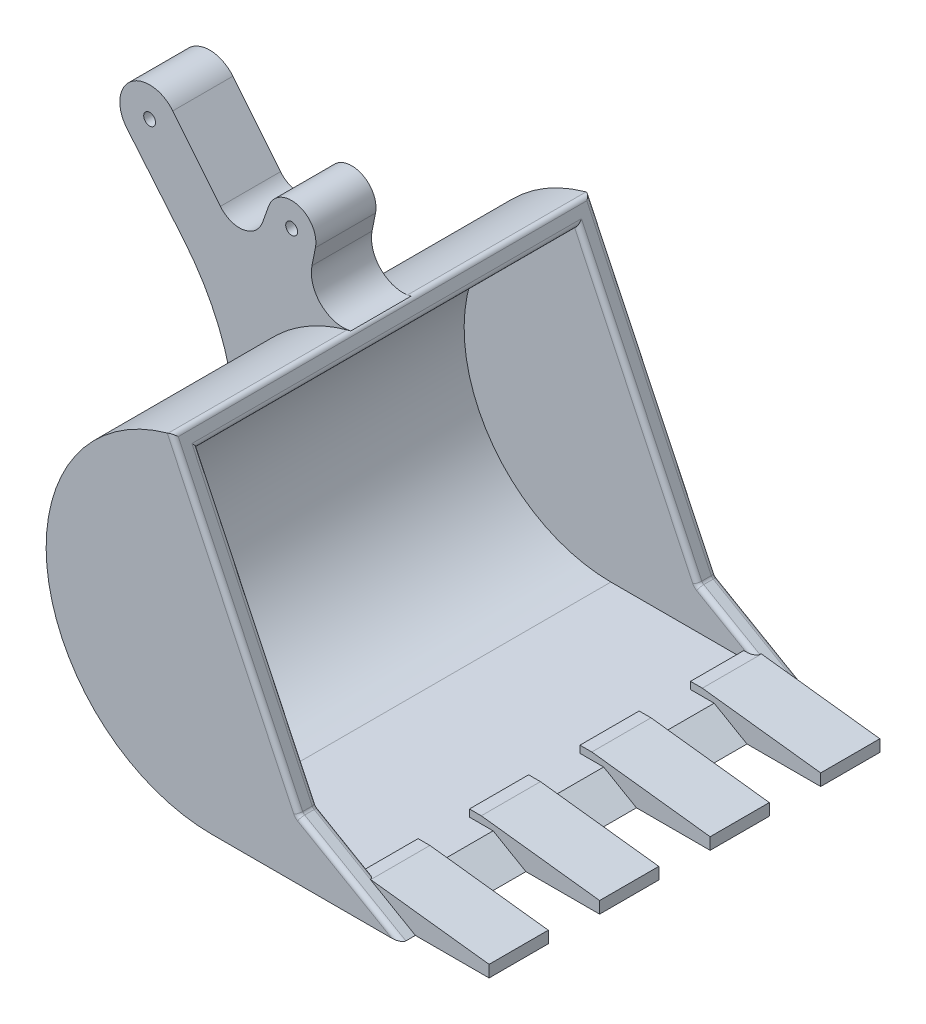
SolidWorks part; units mm, degrees
material "Alloy Steel"
ref_plane "Front Plane" through (0, 0, 0) normal (0, 0, 1) x (1, 0, 0)
ref_plane "Top Plane" through (0, 0, 0) normal (0, 1, 0) x (1, 0, 0)
ref_plane "Right Plane" through (0, 0, 0) normal (1, 0, 0) x (0, 0, -1)
other "Center of Mass"
sketch "Sketch3" plane through (0, 0, 0) normal (0, 0, 1) x (1, 0, 0)
  line L1 (-323.5598, 25) -> (-280.2585, 0)
  line L2 (-360.2585, 0) -> (-280.2585, 0)
  line L6 (-323.5598, 25) -> (-377.1418, 137.9334)
  arc A0 (-360.2585, 0) -> (-377.1418, 137.9334) centre (-360.2585, 70) cw
  point P0 (-355.0693, 139.8074)
  dimension "D1" = 70
  dimension "D2" = 125
  dimension "D3" = 80
  dimension "D4" = 50
  dimension "D5" = 30
extrude "Boss-Extrude1" add sketch "Sketch3" along normal blind 75 and the other way blind 101.6
shell "Shell2" thickness 8
sketch "Sketch5" plane through (0, 0, 0) normal (0, 0, 1) x (1, 0, 0)
  line L0 (-471.8112, 164.8752) -> (-447.6261, 135.8549)
  line L1 (-392.0864, 160.922) -> (-393.5507, 153.6017)
  line L2 (-452.3551, 180.8486) -> (-432.2396, 155.9766)
  line L3 (-411.7956, 166.3923) -> (-414.4462, 158.9945)
  arc A0 (-377.1418, 137.9334) -> (-360.2585, 0) centre (-360.2585, 70) ccw construction
  arc A1 (-432.2396, 155.9766) -> (-414.4462, 158.9945) centre (-424.191, 162.486) ccw
  arc A2 (-427.0333, 91.003) -> (-377.1418, 137.9334) centre (-360.2585, 70) cw
  arc A3 (-452.3551, 180.8486) -> (-471.8112, 164.8752) centre (-462.1418, 172.9334) ccw
  arc A5 (-411.7956, 166.3923) -> (-392.0864, 160.922) centre (-402.1418, 162.9334) cw
  arc A6 (-393.5507, 153.6017) -> (-377.1418, 137.9334) centre (-380.3811, 150.9674) ccw
  arc A8 (-447.6261, 135.8549) -> (-427.0333, 91.003) centre (-520.1798, 75.39) cw
  point P3 (-335.5895, 182.9557)
  point P4 (-378.4966, 174.1952)
  point P7 (0, 0)
  point P9 (-348.1459, 131.2286)
  point P15 (-366.2029, 207.3007)
  point P18 (-380.0938, 170.9707)
  point P20 (-395.534, 191.1792)
  point P22 (-312.6562, 175.5119)
  point P23 (-377.8231, 168.473)
  point P24 (-372.6404, 208.663)
  point P25 (0, 0)
  point P27 (-453.7481, 155.9016)
  point P28 (-453.5686, 177.9334)
  point P29 (-460.077, 153.2208)
  point P30 (0, 0)
  point P31 (-435.4582, 161.0396)
  point P32 (-451.5955, 172.9334)
  point P34 (-442.2496, 158.7758)
  point P35 (-416.7819, 157.4678)
  point P36 (-449.5549, 172.9334)
  point P37 (-434.6093, 159.7785)
  point P38 (-455.2665, 143.2122)
  point P39 (-427.0333, 91.003)
  point P43 (-447.6261, 135.8549)
  point P44 (-396.168, 152.5647)
  point P45 (0, 0)
  point P46 (-419.881, 155.7953)
  point P47 (-408.4001, 165.5007)
  point P48 (-395.1358, 161.463)
  point P49 (-395.6931, 155.0151)
  point P50 (-418.8686, 155.9766)
  point P51 (-411.7956, 166.3923)
  dimension "D1" = 25
  dimension "D3" = 35
  dimension "D5" = 60
  dimension "D6" = 25
extrude "Boss-Extrude2" add sketch "Sketch5" along normal mid plane 25.4 separate body contours A3 L0 A8 A2 A6 L1 A5 L3 A1 L2
sketch "Sketch8" plane through (0, 0, 0) normal (0, 0, 1) x (1, 0, 0)
  circle A0 centre (-402.1418, 162.9334) radius 2.5
  circle A1 centre (-462.1418, 172.9334) radius 2.5
  dimension "D1" = 5
  dimension "D2" = 5
extrude "Cut-Extrude1" cut sketch "Sketch8" against normal blind 20 and the other way blind 20
move or copy body "Body-Move/Copy4" bodies to move or copy 103 copy no translate (0, 0, -13.3)
move or copy body "Body-Move/Copy6" [suppressed] bodies to move or copy 112 copy yes number of copies 1 translate (0, 0, -50.8)
ref_plane "Plane4" through (0, 0, 77.5) normal (0, 0, 1) x (1, 0, 0)
fillet "Fillet3" radius 2 12 edges at (-301.9091, 12.5, 75) (-301.9091, 12.5, -101.6) (-308.8374, 16.5, -93.6) (-308.8374, 16.5, 67) (-350.3508, 81.4667, 75) (-377.1418, 137.9334, -13.3) (-350.3508, 81.4667, -101.6) (-323.5598, 25, -97.6) (-348.5969, 77.77, -93.6) (-373.634, 130.54, -13.3) (-348.5969, 77.77, 67) (-323.5598, 25, 71)
ref_plane "Plane2" through (0, 0, 77.5) normal (0, 0, 1) x (1, 0, 0)
ref_plane "Plane3" through (0, 0, 155) normal (0, 0, 1) x (1, 0, 0)
sketch "Sketch17" plane through (0, 8, 0) normal (0, 1, 0) x (1, 0, 0)
  line L0 (-294.1149, -44) -> (-304.1149, -44)
  line L1 (-294.1149, -69) -> (-249.1149, -69)
  line L2 (-294.1149, -69) -> (-294.1149, -44) construction
  line L3 (-294.1149, -44) -> (-249.1149, -44)
  line L4 (-249.1149, -69) -> (-249.1149, -44)
  line L5 (-304.1149, -44) -> (-304.1149, -69)
  line L6 (-294.1149, -69) -> (-323.02, -69) construction
  line L7 (-304.1149, -69) -> (-294.1149, -69)
  dimension "D1" = 25
  dimension "D2" = 45
  dimension "D3" = 10
extrude "Boss-Extrude3" add sketch "Sketch17" along normal blind 3 and the other way up to surface other way up to face at (-307.9824, 0, -13.3)
sketch "Sketch18" plane through (0, 0, 69) normal (0, 0, 1) x (1, 0, 0)
  line L0 (-249.1149, 5) -> (-309.1149, 11) construction
  line L1 (-249.1149, 0) -> (-249.1149, 11) construction
  line L2 (-299.3111, 11) -> (-249.1149, 11) construction
  line L3 (-309.1149, 11) -> (-309.1149, 0) construction
  line L4 (-280.2585, 0) -> (-249.1149, 0) construction
  line L5 (-309.1149, 0) -> (-249.1149, 0) construction
  line L6 (-249.1149, 0) -> (-249.1149, 5) construction
  line L7 (-299.1149, 11) -> (-249.1149, 11)
  line L8 (-249.1149, 11) -> (-249.1149, 5)
  line L9 (-249.1149, 5) -> (-299.1149, 11)
  line L10 (-299.1149, 11) -> (-309.1149, 11) construction
  dimension "D1" = 5
  dimension "D2" = 60
  dimension "D3" = 10
extrude "Cut-Extrude4" cut sketch "Sketch18" against normal up to surface (25 mm away) up to face at (-280.1389, 6.3333, 44)
pattern_linear "LPattern2" count 4 spacing 46.7 along (0, 0, -1) of "Boss-Extrude3", "Cut-Extrude4"
